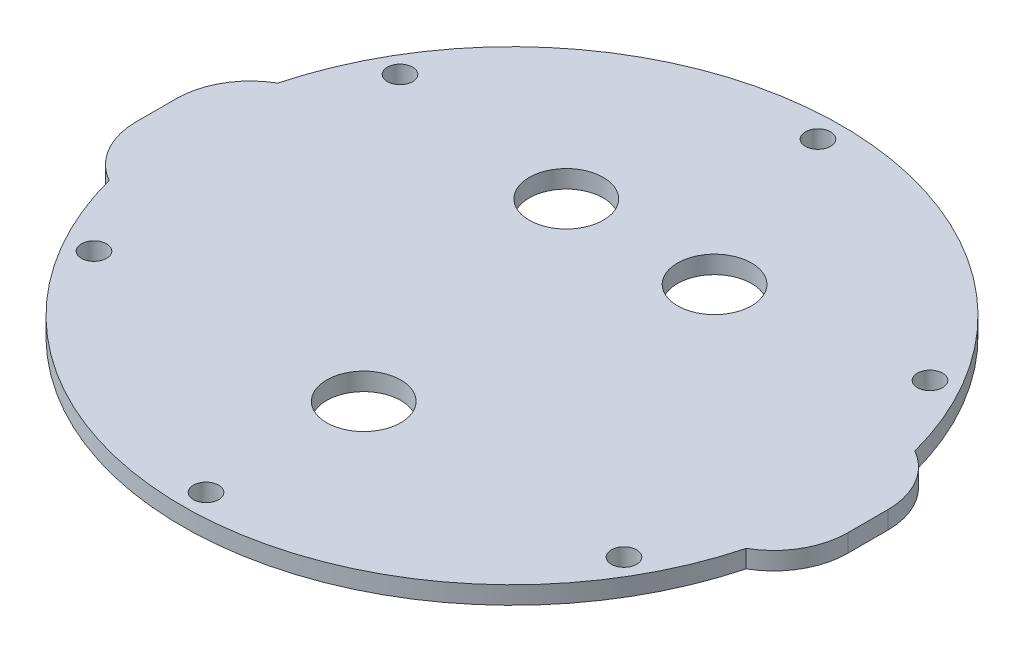
SolidWorks part; units mm, degrees
material "1060 Alloy"
ref_plane "Front Plane" through (0, 0, 0) normal (0, 0, 1) x (1, 0, 0)
ref_plane "Top Plane" through (0, 0, 0) normal (0, 1, 0) x (1, 0, 0)
ref_plane "Right Plane" through (0, 0, 0) normal (1, 0, 0) x (0, 0, -1)
sketch "Sketch1" plane through (0, 0, 0) normal (0, 1, 0) x (1, 0, 0)
  line L0 (-48, 0) -> (48, 0) construction
  line L1 (-38, 12.7) -> (38, 12.7)
  line L2 (-48, 2.7) -> (-48, -2.7)
  line L3 (-38, -12.7) -> (38, -12.7)
  line L4 (48, 2.7) -> (48, -2.7)
  line L5 (0, 12.7) -> (0, -12.7) construction
  circle A0 centre (0, 0) radius 44.45
  arc A1 (38, -12.7) -> (48, -2.7) centre (38, -2.7) ccw
  arc A2 (38, 12.7) -> (48, 2.7) centre (38, 2.7) cw
  arc A3 (-38, 12.7) -> (-48, 2.7) centre (-38, 2.7) ccw
  arc A4 (-38, -12.7) -> (-48, -2.7) centre (-38, -2.7) cw
  point P11 (0, 0)
  point P18 (-48, 12.7)
  point P21 (-48, -12.7)
  dimension "D1" = 88.9
  dimension "D2" = 48
  dimension "D4" = 10
  dimension "D3" = 25.4
extrude "Boss-Extrude1" add sketch "Sketch1" along normal blind 2.4 contours A4 A0 A3 L2 | A4 L3 A1 A0 A2 L1 A3 | L3 A4 A0 A1 | A3 L1 A2 A0 | A2 A0 A1 L4
sketch "Sketch2" plane through (0, 2.4, 0) normal (0, 1, 0) x (1, 0, 0)
  circle A0 centre (0, 0) radius 41.275 construction
  dimension "D1" = 82.55
hole_wizard "M3 Clearance Hole1" positions "3DSketch2" profile "Sketch4" hole size "M3" standard "ANSI Metric" end condition through all
sketch3d "3DSketch2"
  line L0 (0, 2.4, -41.275) -> (0, 2.4, 41.275) construction
  line L2 (-41.275, 2.4, 0) -> (41.275, 2.4, 0) construction
  circle A0 centre (0, 2.4, 0) radius 41.275 construction
  point P0 (0, 2.4, -41.275)
  point P4 (0, 43.675, 0)
  point P15 (0, 2.4, 0)
  point P16 (0, 2.4, 0)
sketch "Sketch4" plane through (0, 2.4, -41.275) normal (1, 0, 0) x (0, 0, 1)
  line L0 (0, 0) -> (0, 2.4)
  line L1 (0, 2.4) -> (1.7, 2.4)
  line L2 (1.7, 2.4) -> (1.7, 0)
  line L5 (1.7, 0) -> (0, 0)
  line L11 (0, -6.35) -> (0, 107.95) construction
  dimension "Thru Hole Dia." = 3.4
  dimension "Thru Hole Depth" = 2.4
pattern_circular "CirPattern1" count 6 over 360 about axis through (0, 0, 0) along (0, 1, 0) of "M3 Clearance Hole1"
sketch "Sketch8" plane through (0, 2.4, 0) normal (0, 1, 0) x (1, 0, 0)
  line L0 (0, 44.45) -> (0, -44.45) construction
  line L1 (-10, 17.3205) -> (10, 17.3205) construction
  arc A0 (42.9691, 11.378) -> (-42.9691, 11.378) centre (0, 0) ccw construction
  arc A1 (-42.9691, -11.378) -> (42.9691, -11.378) centre (0, 0) ccw construction
  circle A2 centre (-10, 17.3205) radius 5
  circle A3 centre (0, 0) radius 31.75 construction
  circle A4 centre (10, 17.3205) radius 5
  circle A5 centre (-10, 17.3205) radius 9.017 construction
  circle A6 centre (10, 17.3205) radius 9.017 construction
  circle A7 centre (0, -20) radius 5
  dimension "D1" = 10
  dimension "D3" = 63.5
  dimension "D5" = 18.034
  dimension "D2" = 20
  dimension "D4" = 10
  dimension "D6" = 20
extrude "Cut-Extrude2" cut sketch "Sketch8" against normal through all
